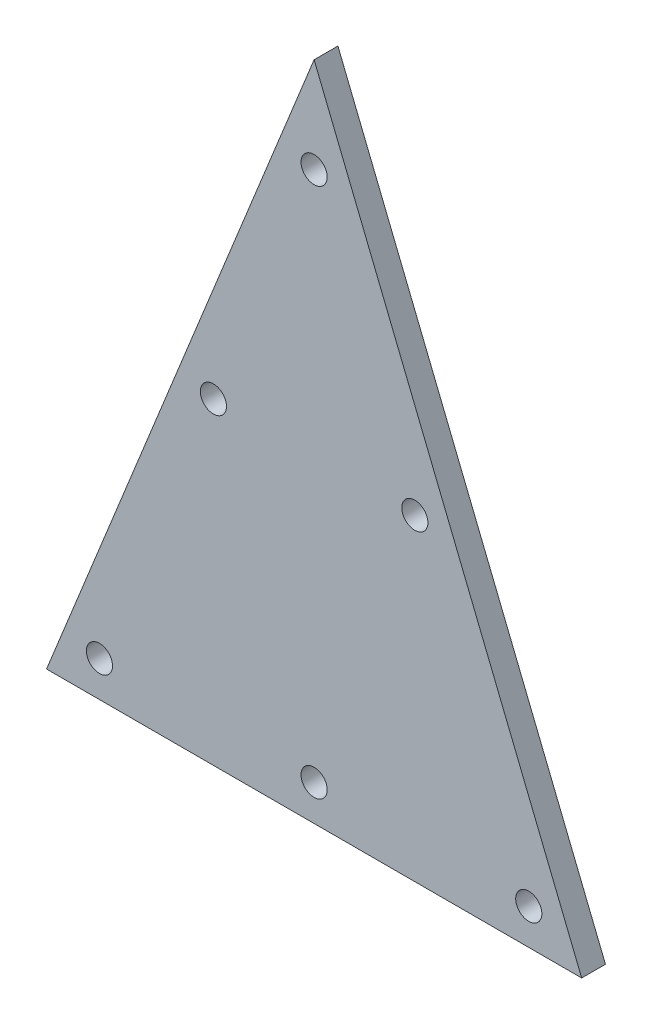
SolidWorks part; units mm, degrees
material "PVC rigide"
ref_plane "Plan de face" through (0, 0, 0) normal (0, 0, 1) x (1, 0, 0)
ref_plane "Plan de dessus" through (0, 0, 0) normal (0, 1, 0) x (1, 0, 0)
ref_plane "Plan de droite" through (0, 0, 0) normal (1, 0, 0) x (0, 0, -1)
sketch "Esquisse1" plane through (0, 0, 0) normal (0, 0, 1) x (1, 0, 0)
  line L0 (0, 0) -> (45, 0)
  line L1 (45, 0) -> (22.5, 55.6215)
  line L2 (22.5, 55.6215) -> (0, 0)
  line L3 (11.25, 27.8107) -> (22.5, 23.2599) construction
  line L4 (33.75, 27.8107) -> (22.5, 23.2599) construction
  circle A0 centre (22.5, 3) radius 1.1
  circle A1 centre (14.0311, 26.6857) radius 1.1
  circle A2 centre (30.9689, 26.6857) radius 1.1
  circle A3 centre (4.4497, 3) radius 1.1
  circle A4 centre (22.5, 47.6215) radius 1.1
  circle A5 centre (40.5503, 3) radius 1.1
  dimension "D4" = 2.2
  dimension "D5" = 2.2
  dimension "D6" = 2.2
  dimension "D11" = 2.2
  dimension "D12" = 3
  dimension "D16" = 2.2
  dimension "D17" = 2.2
  dimension "D1" = 45
  dimension "D2" = 60
  dimension "D3" = 60
  dimension "D7" = 3
  dimension "D8" = 22.5
  dimension "D9" = 3
  dimension "D10" = 3
  dimension "D13" = 3
  dimension "D14" = 3
  dimension "D15" = 3
  dimension "D18" = 3
  dimension "D19" = 3
extrude "Boss.-Extru.1" add sketch "Esquisse1" along normal blind 2
